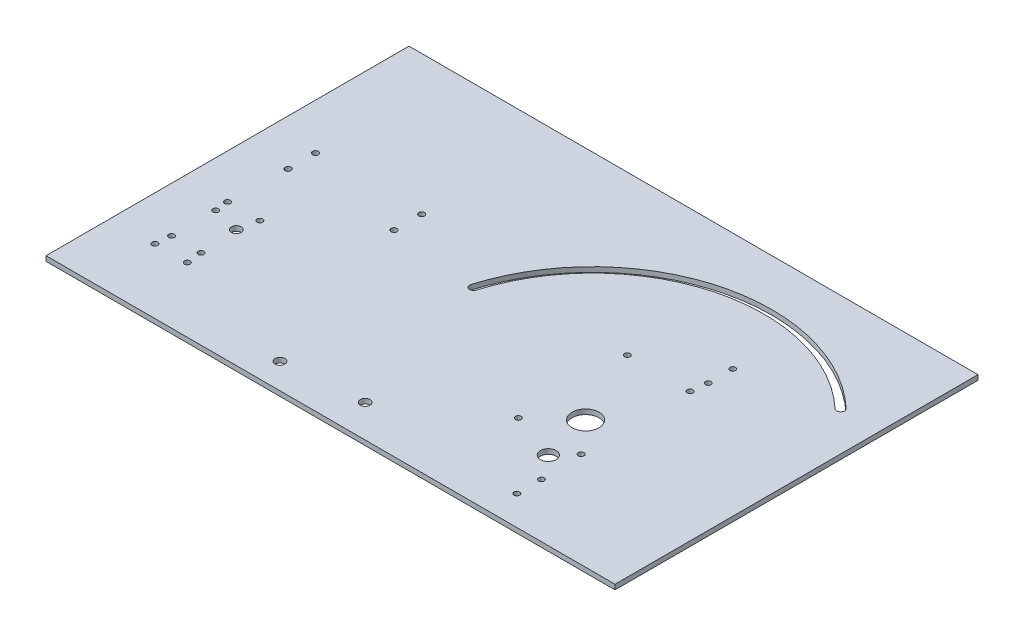
SolidWorks part; units mm, degrees
ref_plane "Front Plane" through (0, 0, 0) normal (0, 0, 1) x (1, 0, 0)
ref_plane "Top Plane" through (0, 0, 0) normal (0, 1, 0) x (1, 0, 0)
ref_plane "Right Plane" through (0, 0, 0) normal (1, 0, 0) x (0, 0, -1)
sketch "Sketch1" plane through (0, 0, 0) normal (0, 1, 0) x (1, 0, 0)
  line L1 (-158.75, 88.9) -> (158.75, 88.9)
  line L2 (-158.75, 88.9) -> (-158.75, -88.9)
  line L3 (-158.75, -88.9) -> (158.75, -88.9)
  line L4 (158.75, 88.9) -> (158.75, -88.9)
  line L5 (-158.75, 88.9) -> (158.75, -88.9) construction
  line L6 (-158.75, -88.9) -> (158.75, 88.9) construction
  circle A0 centre (-111.76, -12.7) radius 3.175
  circle A1 centre (107.95, -6.35) radius 8.7313
  circle A4 centre (-129.032, 55.88) radius 1.905
  circle A5 centre (-60.452, 55.88) radius 1.905
  circle A7 centre (-129.032, 38.1) radius 1.905
  circle A8 centre (-60.452, 38.1) radius 1.905
  point P0 (0, 0)
  dimension "D3" = 6.35
  dimension "D4" = 17.4625
  dimension "D14" = 3.81
  dimension "D17" = 17.78
  dimension "D1" = 317.5
  dimension "D2" = 177.8
  dimension "D5" = 46.99
  dimension "D6" = 266.7
  dimension "D7" = 95.25
  dimension "D8" = 76.2
  dimension "D13" = 29.718
  dimension "D15" = 68.58
  dimension "D16" = 127
extrude "Boss-Extrude1" add sketch "Sketch1" along normal blind 3.175
sketch "Sketch2" plane through (0, 3.175, 0) normal (0, 1, 0) x (1, 0, 0)
  line L0 (-158.75, 88.9) -> (-158.75, -88.9) construction
  line L1 (-158.75, -88.9) -> (158.75, -88.9) construction
  circle A0 centre (-89.0817, -33.177) radius 1.905
  circle A1 centre (-132.1376, -36.4483) radius 1.905
  dimension "D1" = 3.81
  dimension "D2" = 69.6683
  dimension "D3" = 52.4517
  dimension "D4" = 55.723
  dimension "D5" = 43.18
extrude "Cut-Extrude1" [suppressed] cut sketch "Sketch2" against normal through all
sketch "Sketch3" plane through (0, 0, 0) normal (0, -1, 0) x (-1, 0, 0)
  line L0 (158.75, -88.9) -> (-158.75, -88.9) construction
  line L1 (158.75, 88.9) -> (158.75, -88.9) construction
  circle A0 centre (23.8295, -72.39) radius 3.175
  circle A1 centre (-26.7643, -67.818) radius 3.175
  dimension "D1" = 6.35
  dimension "D2" = 4.572
  dimension "D3" = 16.51
  dimension "D4" = 185.5143
  dimension "D5" = 50.8
extrude "Cut-Extrude2" cut sketch "Sketch3" against normal through all
sketch "Sketch4" plane through (0, 3.175, 0) normal (0, 1, 0) x (1, 0, 0)
  line L0 (-158.75, -88.9) -> (158.75, -88.9) construction
  line L1 (158.75, 88.9) -> (133.35, 88.9)
  line L2 (158.75, 88.9) -> (158.75, -88.9)
  line L3 (158.75, -88.9) -> (133.35, -88.9)
  line L4 (133.35, 88.9) -> (133.35, -88.9)
  dimension "D1" = 25.4
extrude "Cut-Extrude3" cut sketch "Sketch4" against normal through all
sketch "Sketch5" plane through (0, 3.175, 0) normal (0, 1, 0) x (1, 0, 0)
  line L0 (133.35, 88.9) -> (-158.75, 88.9) construction
  line L1 (133.35, 88.9) -> (133.35, -88.9) construction
  circle A0 centre (115.57, -38.1) radius 5.08
  dimension "D3" = 10.16
  dimension "D1" = 127
  dimension "D2" = 17.78
extrude "Cut-Extrude4" cut sketch "Sketch5" against normal through all
sketch "Sketch6" plane through (0, 0, 0) normal (0, -1, 0) x (1, 0, 0)
  line L0 (-158.75, 88.9) -> (133.35, 88.9) construction
  line L1 (133.35, -88.9) -> (133.35, 88.9) construction
  line L2 (133.35, -88.9) -> (-158.75, -88.9) construction
  circle A0 centre (127, 69.85) radius 1.8034
  circle A2 centre (127, 53.975) radius 1.8034
  circle A3 centre (127, -53.975) radius 1.8034
  circle A4 centre (127, -69.85) radius 1.8034
  dimension "D4" = 3.6068
  dimension "D5" = 6.35
  dimension "D1" = 15.875
  dimension "D2" = 19.05
  dimension "D3" = 6.35
  dimension "D6" = 15.875
  dimension "D7" = 19.05
extrude "Cut-Extrude5" cut sketch "Sketch6" against normal through all
sketch "Sketch7" plane through (0, 3.175, 0) normal (0, 1, 0) x (1, 0, 0)
  line L0 (133.35, 88.9) -> (133.35, -88.9) construction
  line L1 (133.35, 88.9) -> (-158.75, 88.9) construction
  line L2 (-158.75, 88.9) -> (-158.75, -88.9) construction
  line L3 (-158.75, -88.9) -> (133.35, -88.9) construction
  circle A1 centre (125.73, 43.4975) radius 1.8415
  circle A2 centre (85.09, 43.4975) radius 1.8415
  circle A3 centre (85.09, -26.9875) radius 1.8415
  circle A4 centre (125.73, -26.9875) radius 1.8415
  circle A5 centre (-130.175, -46.99) radius 1.8415
  circle A6 centre (-109.22, -46.99) radius 1.8415
  circle A7 centre (-129.2225, -37.1475) radius 1.8415
  circle A8 centre (-110.1725, -37.1475) radius 1.8415
  circle A9 centre (-129.2225, -8.5725) radius 1.8415
  circle A10 centre (-130.175, 0) radius 1.8415
  circle A11 centre (-109.22, 0) radius 1.8415
  dimension "D1" = 7.62
  dimension "D5" = 3.683
  dimension "D10" = 3.683
  dimension "D15" = 3.683
  dimension "D2" = 40.64
  dimension "D3" = 70.485
  dimension "D4" = 61.9125
  dimension "D6" = 28.575
  dimension "D7" = 20.955
  dimension "D8" = 0.9525
  dimension "D9" = 19.05
  dimension "D11" = 88.9
  dimension "D12" = 8.5725
  dimension "D13" = 28.575
  dimension "D14" = 9.8425
extrude "Cut-Extrude6" cut sketch "Sketch7" against normal through all
sketch "Sketch8" plane through (0, 0, 0) normal (0, -1, 0) x (1, 0, 0)
  line L1 (-158.75, -88.9) -> (-158.75, 88.9) construction
  line L2 (-158.75, 88.9) -> (133.35, 88.9) construction
  line L3 (133.35, 88.9) -> (133.35, -88.9)
  line L4 (133.35, -88.9) -> (-158.75, -88.9) construction
  line L5 (133.35, -88.9) -> (-158.75, -88.9)
  line L6 (-158.75, -88.9) -> (-158.75, -146.05)
  line L7 (-158.75, -146.05) -> (209.55, -146.05)
  line L8 (209.55, -146.05) -> (209.55, 88.9)
  line L9 (209.55, 88.9) -> (133.35, 88.9)
  line L12 (133.35, -88.9) -> (133.35, 88.9) construction
  dimension "D1" = 76.2
  dimension "D2" = 57.15
extrude "Boss-Extrude2" add sketch "Sketch8" against normal through all
sketch "Sketch9" plane through (0, 0, 0) normal (0, -1, 0) x (1, 0, 0)
  line L0 (209.55, -146.05) -> (209.55, 88.9) construction
  line L1 (-158.75, 88.9) -> (209.55, 88.9) construction
  arc A0 (185.8872, -84.403) -> (182.4128, -80.697) centre (184.15, -82.55) ccw
  arc A1 (-0.1844, -31.0322) -> (-5.0573, -32.4678) centre (-2.6208, -31.75) ccw
  circle A2 centre (106.4105, 0.3734) radius 113.665 construction
  arc A3 (182.4128, -80.697) -> (-0.1844, -31.0322) centre (106.4105, 0.3734) cw
  arc A4 (185.8872, -84.403) -> (-5.0573, -32.4678) centre (106.4105, 0.3734) cw
  arc A5 (-5.0573, -32.4678) -> (-1.8758, -34.1783) centre (-2.6208, -31.75) ccw construction
  arc A6 (-1.8758, -34.1783) -> (-0.1844, -31.0322) centre (-2.6208, -31.75) ccw construction
  arc A7 (182.2777, -84.2664) -> (185.8872, -84.403) centre (184.15, -82.55) ccw construction
  arc A8 (182.4128, -80.697) -> (182.2777, -84.2664) centre (184.15, -82.55) ccw construction
  point P1 (0, 0)
  point P3 (0, 0)
  point P4 (0, 0)
  point P16 (0, 0)
  point P21 (0, 0)
  point P22 (0, 0)
  point P23 (0, 0)
  dimension "D1" = 5.08
  dimension "D6" = 227.33
  dimension "D2" = 25.4
  dimension "D3" = 171.45
  dimension "D4" = 120.65
  dimension "D5" = 186.7708
extrude "Cut-Extrude7" cut sketch "Sketch9" against normal through all
